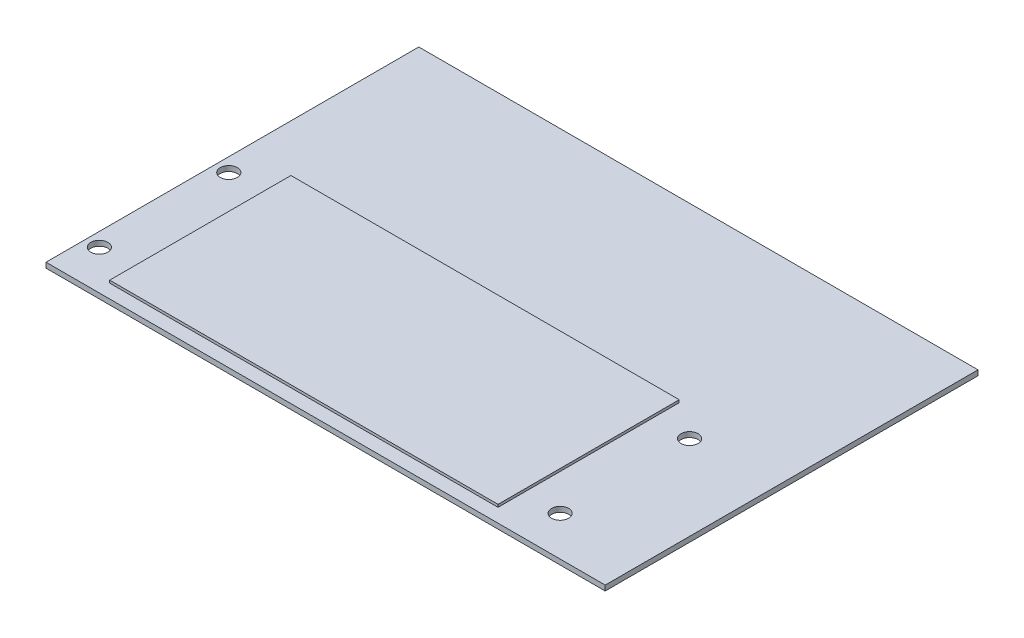
SolidWorks part; units mm, degrees
ref_plane "Front Plane" through (0, 0, 0) normal (0, 0, 1) x (1, 0, 0)
ref_plane "Top Plane" through (0, 0, 0) normal (0, 1, 0) x (1, 0, 0)
ref_plane "Right Plane" through (0, 0, 0) normal (1, 0, 0) x (0, 0, -1)
sketch "Sketch1" plane through (0, 0, 0) normal (0, 1, 0) x (1, 0, 0)
  line L1 (-47.15, 51.85) -> (60.85, 51.85)
  line L2 (-47.15, 51.85) -> (-47.15, -20.15)
  line L3 (-47.15, -20.15) -> (60.85, -20.15)
  line L4 (60.85, 51.85) -> (60.85, -20.15)
  line L5 (-44.5, -12.5) -> (44.5, 12.5) construction
  line L6 (-44.5, 12.5) -> (44.5, 12.5) construction
  line L7 (-44.5, 12.5) -> (-44.5, -12.5) construction
  line L8 (-44.5, -12.5) -> (44.5, -12.5) construction
  line L9 (44.5, 12.5) -> (44.5, -12.5) construction
  circle A0 centre (-44.5, 12.5) radius 1.65
  circle A1 centre (-44.5, -12.5) radius 1.65
  circle A2 centre (44.5, 12.5) radius 1.65
  circle A3 centre (44.5, -12.5) radius 1.65
  point P4 (0, 0)
  dimension "D3" = 3.3
  dimension "D4" = 6
  dimension "D5" = 1
  dimension "D1" = 72
  dimension "D2" = 108
  dimension "D6" = 25
  dimension "D7" = 89
extrude "Boss-Extrude1" add sketch "Sketch1" along normal blind 1
sketch "Sketch2" plane through (0, 1, 0) normal (0, 1, 0) x (1, 0, 0)
  line L1 (37.5, 17.5) -> (-37.5, 17.5)
  line L2 (37.5, 17.5) -> (37.5, -17.5)
  line L3 (37.5, -17.5) -> (-37.5, -17.5)
  line L4 (-37.5, 17.5) -> (-37.5, -17.5)
  line L5 (37.5, 17.5) -> (-37.5, -17.5) construction
  line L6 (37.5, -17.5) -> (-37.5, 17.5) construction
  point P0 (0, 0)
  dimension "D1" = 35
  dimension "D2" = 75
extrude "Boss-Extrude2" add sketch "Sketch2" along normal blind 0.5
sketch "Sketch3" plane through (0, 1.5, 0) normal (0, 1, 0) x (1, 0, 0)
  line L1 (-63, -53) -> (63, -53)
  line L2 (-63, -53) -> (-63, 53)
  line L3 (-63, 53) -> (63, 53)
  line L4 (63, -53) -> (63, 53)
  line L5 (-63, -53) -> (63, 53) construction
  line L6 (-63, 53) -> (63, -53) construction
  point P0 (0, 0)
  dimension "D1" = 126
  dimension "D2" = 106
